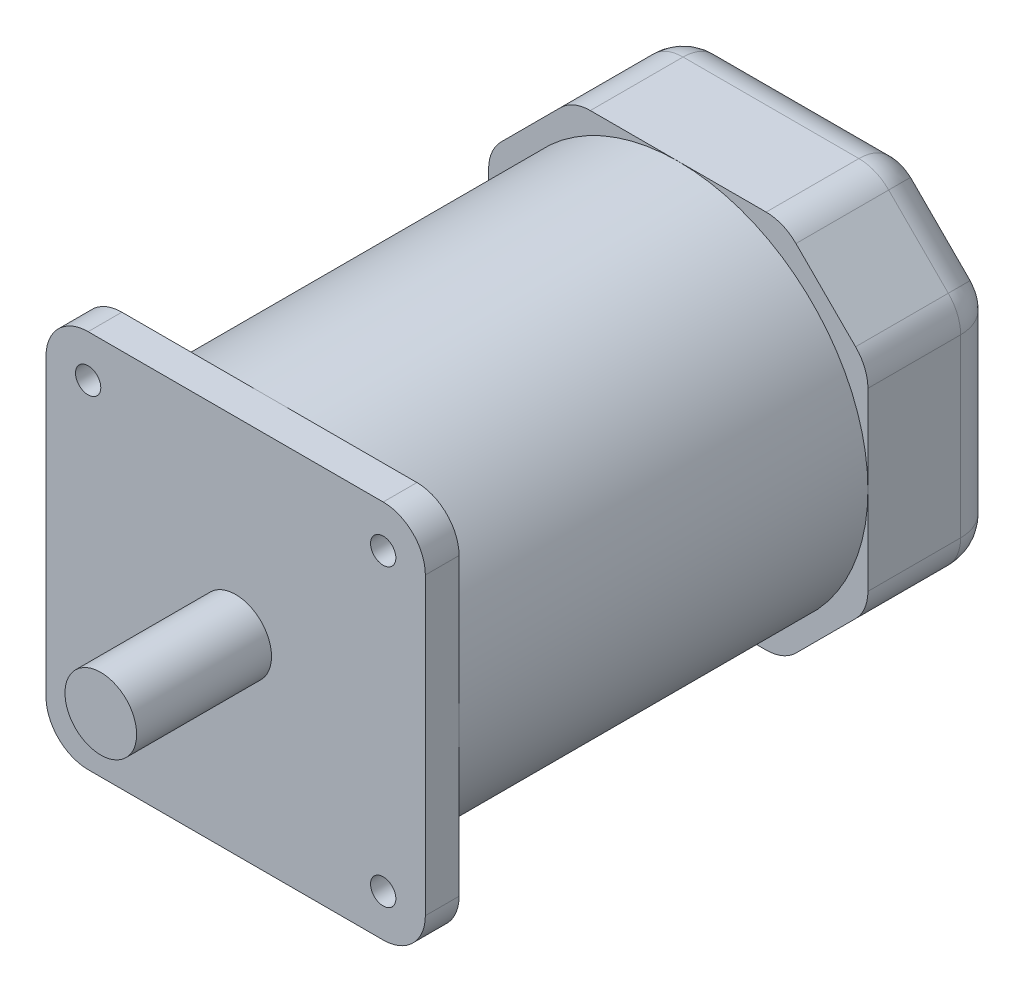
SolidWorks part; units mm, degrees
ref_plane "Alzado" through (0, 0, 0) normal (0, 0, 1) x (1, 0, 0)
ref_plane "Planta" through (0, 0, 0) normal (0, 1, 0) x (1, 0, 0)
ref_plane "Vista lateral" through (0, 0, 0) normal (1, 0, 0) x (0, 0, -1)
sketch "Sketch1" plane through (0, 0, 0) normal (0, 0, 1) x (1, 0, 0)
  line L1 (45, -45) -> (-45, -45)
  line L2 (45, -45) -> (45, 45)
  line L3 (45, 45) -> (-45, 45)
  line L4 (-45, -45) -> (-45, 45)
  line L5 (45, -45) -> (-45, 45) construction
  line L6 (45, 45) -> (-45, -45) construction
  point P0 (0, 0)
  dimension "D1" = 90
extrude "Boss-Extrude1" add sketch "Sketch1" along normal blind 8
fillet "Fillet1" radius 10 4 edges at (-45, -45, 4) (45, -45, 4) (45, 45, 4) (-45, 45, 4)
sketch "Sketch2" plane through (0, 0, 8) normal (0, 0, 1) x (1, 0, 0)
  circle A0 centre (0, 0) radius 45
extrude "Boss-Extrude2" add sketch "Sketch2" against normal blind 137
sketch "Sketch3" plane through (0, 0, 8) normal (0, 0, 1) x (1, 0, 0)
  circle A0 centre (0, 0) radius 8.5
  dimension "D1" = 17
extrude "Boss-Extrude3" add sketch "Sketch3" along normal blind 32
hole_wizard "Ø6.0 mm Dowel Holes1" positions "Sketch6" profile "Sketch7" hole size "Ø6.0" standard "ANSI Metric"
sketch "Sketch6" plane through (0, 0, 8) normal (0, 0, 1) x (1, 0, 0)
  arc A0 (-35, 45) -> (-45, 35) centre (-35, 35) ccw construction
  arc A1 (45, 35) -> (35, 45) centre (35, 35) ccw construction
  arc A4 (35, -45) -> (45, -35) centre (35, -35) ccw construction
  arc A5 (-45, -35) -> (-35, -45) centre (-35, -35) ccw construction
  point P0 (-35, 35)
  point P2 (35, 35)
  point P4 (35, -35)
  point P6 (-35, -35)
  point P13 (0, 0)
  point P26 (0, 0)
sketch "Sketch7" plane through (-35, 35, 8) normal (1, 0, 0) x (0, -1, 0)
  line L0 (0, 0) -> (0, 31.8026)
  line L1 (0, 31.8026) -> (3, 30)
  line L2 (3, 30) -> (3, 0)
  line L5 (3, 0) -> (0, 0)
  line L10 (0, 31.8026) -> (-3, 30) construction
  line L11 (0, -6.35) -> (0, 107.95) construction
  dimension "Hole Dia." = 6
  dimension "Hole Depth" = 30
  dimension "Drill Angle" = 118
sketch "Sketch8" plane through (0, 0, -129) normal (0, 0, -1) x (-1, 0, 0)
  line L0 (-35, 45) -> (0, 45) construction
  line L1 (45, -45) -> (-45, -45)
  line L2 (45, -45) -> (45, 45)
  line L3 (45, 45) -> (-45, 45)
  line L4 (-45, -45) -> (-45, 45)
  line L5 (45, -45) -> (-45, 45) construction
  line L6 (45, 45) -> (-45, -45) construction
  point P0 (0, 0)
extrude "Boss-Extrude4" add sketch "Sketch8" against normal blind 32
chamfer "Chamfer2" distance 20 angle 45 4 edges at (45, -45, -113) (-45, -45, -113) (-45, 45, -113) (45, 45, -113)
fillet "Fillet2" radius 10 16 edges at (35, 35, -129) (0, 45, -129) (-35, 35, -129) (-45, 0, -129) (-35, -35, -129) (0, -45, -129) (35, -35, -129) (45, 0, -129) (-25, 45, -113) (-45, -25, -113) (-25, -45, -113) (-45, 25, -113) (25, -45, -113) (45, -25, -113) (25, 45, -113) (45, 25, -113)
